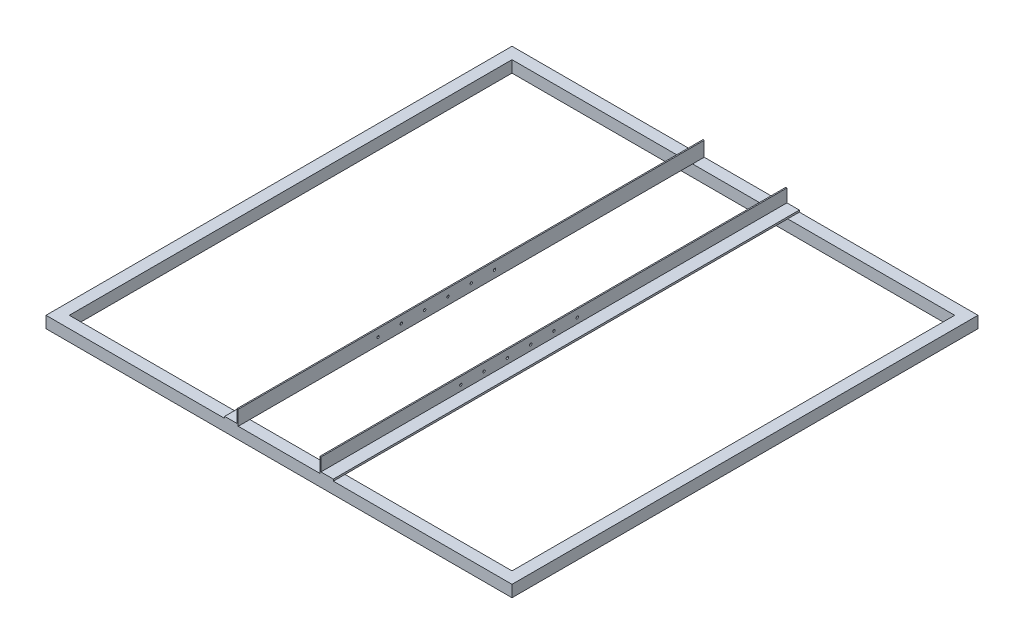
SolidWorks part; units mm, degrees
ref_plane "Front Plane" through (0, 0, 0) normal (0, 0, 1) x (1, 0, 0)
ref_plane "Top Plane" through (0, 0, 0) normal (0, 1, 0) x (1, 0, 0)
ref_plane "Right Plane" through (0, 0, 0) normal (1, 0, 0) x (0, 0, -1)
sketch "Sketch1" plane through (0, 0, 0) normal (0, 1, 0) x (1, 0, 0)
  line L1 (-400, 400) -> (400, 400)
  line L2 (-400, 400) -> (-400, -400)
  line L3 (-400, -400) -> (400, -400)
  line L4 (400, 400) -> (400, -400)
  line L5 (-400, 400) -> (400, -400) construction
  line L6 (-400, -400) -> (400, 400) construction
  line L7 (380, 380) -> (-380, 380)
  line L8 (380, 380) -> (380, -380)
  line L9 (380, -380) -> (-380, -380)
  line L10 (-380, 380) -> (-380, -380)
  line L11 (380, 380) -> (-380, -380) construction
  line L12 (380, -380) -> (-380, 380) construction
  point P0 (0, 0)
  point P6 (0, 0)
  dimension "D1" = 800
  dimension "D2" = 800
  dimension "D3" = 760
extrude "Boss-Extrude1" add sketch "Sketch1" along normal blind 20
sketch "Sketch2" plane through (0, 20, 0) normal (0, 1, 0) x (1, 0, 0)
  line L0 (0, 400) -> (0, -400) construction
  line L1 (400, 400) -> (-400, 400) construction
  line L2 (-400, -400) -> (400, -400) construction
  line L3 (0, 244.4807) -> (70, 244.4807) construction
  line L4 (-70, -400) -> (-72, -400)
  line L5 (70, 400) -> (72, 400)
  line L6 (70, 400) -> (70, -400)
  line L7 (70, -400) -> (72, -400)
  line L8 (72, 400) -> (72, -400)
  line L9 (-70, 400) -> (-72, 400)
  line L10 (-70, 400) -> (-70, -400)
  line L11 (-72, 400) -> (-72, -400)
  dimension "D1" = 70
  dimension "D2" = 2
extrude "Boss-Extrude2" add sketch "Sketch2" along normal blind 25.3
sketch "Sketch3" plane through (-72, 0, 0) normal (-1, 0, 0) x (0, 0, 1)
  line L0 (-400, 32.65) -> (400, 32.65) construction
  line L1 (-400, 45.3) -> (-400, 20) construction
  line L2 (400, 45.3) -> (400, 20) construction
  circle A0 centre (0, 32.65) radius 2.1
  circle A1 centre (-40, 32.65) radius 2.1
  circle A2 centre (40, 32.65) radius 2.1
  circle A3 centre (80, 32.65) radius 2.1
  circle A4 centre (120, 32.65) radius 2.1
  circle A5 centre (160, 32.65) radius 2.1
  point P8 (40, 32.65)
  point P9 (80, 32.65)
  point P10 (120, 32.65)
  point P11 (160, 32.65)
  point P12 (-40, 32.65)
  dimension "D1" = 4.2
  dimension "D6" = 4.2
  dimension "D7" = 4.2
  dimension "D8" = 4.2
  dimension "D9" = 4.2
  dimension "D10" = 4.2
  dimension "D2" = 40
  dimension "D3" = 80
  dimension "D4" = 40
  dimension "D5" = 40
extrude "Cut-Extrude2" cut sketch "Sketch3" against normal blind 158
sketch "Sketch4" plane through (0, 20, 0) normal (0, 1, 0) x (1, 0, 0)
  line L0 (72, -400) -> (400, -400) construction
  line L1 (72, 400) -> (93.3, 400)
  line L2 (72, 400) -> (72, -400)
  line L3 (72, -400) -> (93.3, -400)
  line L4 (93.3, 400) -> (93.3, -400)
  line L5 (-72, 400) -> (-400, 400) construction
  line L6 (-72, -400) -> (-93.3, -400)
  line L7 (-72, -400) -> (-72, 400)
  line L8 (-72, 400) -> (-93.3, 400)
  line L9 (-93.3, -400) -> (-93.3, 400)
  dimension "D1" = 21.3
extrude "Boss-Extrude3" add sketch "Sketch4" along normal blind 3.09
